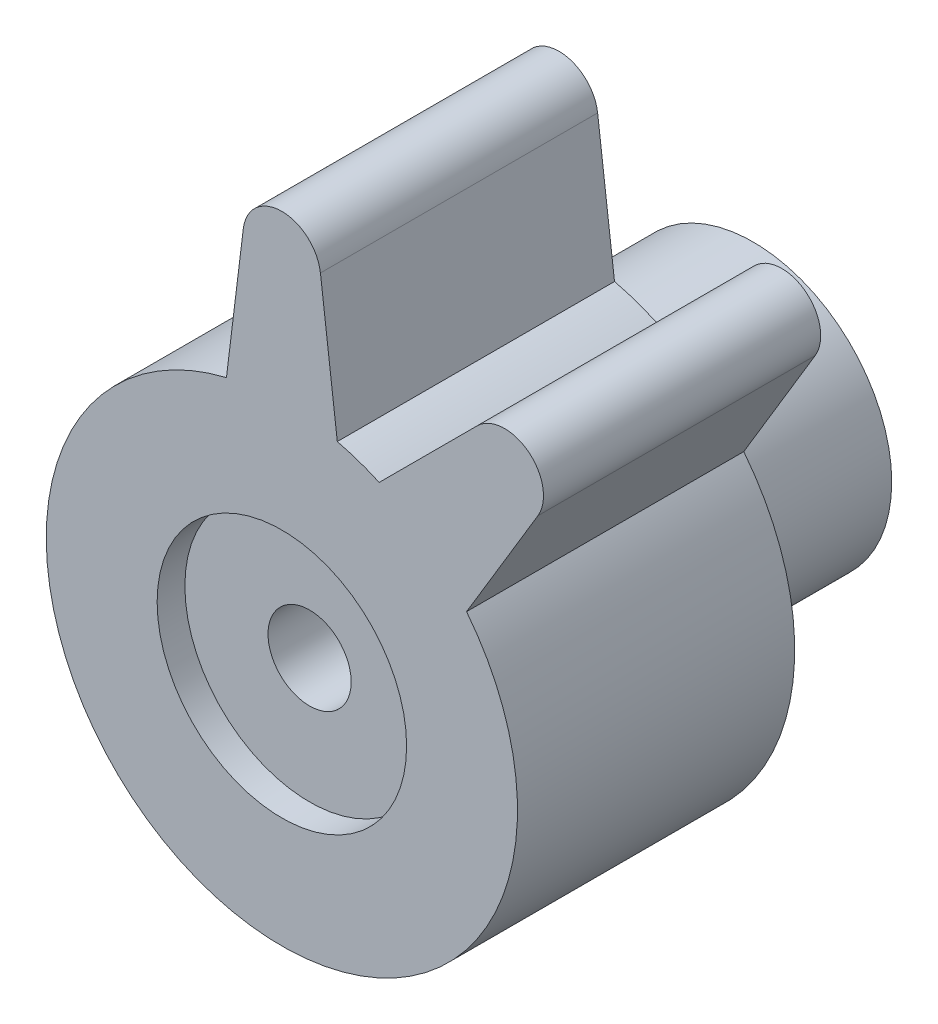
SolidWorks part; units mm, degrees
ref_plane "Front Plane" through (0, 0, 0) normal (0, 0, 1) x (1, 0, 0)
ref_plane "Top Plane" through (0, 0, 0) normal (0, 1, 0) x (1, 0, 0)
ref_plane "Right Plane" through (0, 0, 0) normal (1, 0, 0) x (0, 0, -1)
sketch "Sketch1" plane through (0, 0, 0) normal (0, 0, 1) x (1, 0, 0)
  line L0 (0, 0) -> (0, 51.188) construction
  line L1 (-2, 8.2614) -> (-1.3907, 13.2241)
  line L2 (2, 8.2614) -> (1.3907, 13.2241)
  line L3 (0, 0) -> (22.4184, 65.1077) construction
  line L4 (6.6622, 5.2787) -> (9.2374, 9.5646)
  line L5 (0, 0) -> (31.5145, 40.3367) construction
  line L6 (3.5102, 7.7414) -> (7.0457, 11.2769)
  circle A0 centre (0, 0) radius 8.5
  circle A1 centre (0, 0) radius 1.5
  arc A2 (-1.3907, 13.2241) -> (1.3907, 13.2241) centre (0, 13.0533) cw
  arc A3 (9.2374, 9.5646) -> (7.0457, 11.2769) centre (8.0364, 10.2862) ccw
  circle A4 centre (0, 0) radius 12 construction
  dimension "D1" = 24
  dimension "D2" = 17
  dimension "D3" = 3
  dimension "D4" = 7
  dimension "D7" = 5
  dimension "D5" = 4
  dimension "D6" = 19
extrude "Boss-Extrude1" add sketch "Sketch1" along normal blind 10
sketch "Sketch5" plane through (0, 0, 0) normal (0, 0, -1) x (-1, 0, 0)
  line L0 (1.95, -2.6) -> (-1.95, -2.6)
  circle A0 centre (0, 0) radius 3.25
  circle A1 centre (0, 0) radius 5
  dimension "D1" = 10
  dimension "D2" = 6.5
  dimension "D3" = 2.6
extrude "Boss-Extrude3" add sketch "Sketch5" along normal blind 7 contours A1 A0 | L0 A0
sketch "Sketch8" plane through (0, 0, 10) normal (0, 0, 1) x (1, 0, 0)
  circle A0 centre (0, 0) radius 4.5
  dimension "D1" = 9
extrude "Cut-Extrude2" cut sketch "Sketch8" against normal blind 1
sketch "Sketch9" plane through (0, -2.6, 0) normal (0, 1, 0) x (1, 0, 0)
  line L0 (-1.95, 7) -> (1.95, 7) construction
  line L2 (-1.95, 4) -> (1.95, 4) construction
  line L3 (-1.95, 7) -> (-1.95, 0) construction
  line L4 (1.95, 7) -> (1.95, 0) construction
  circle A0 centre (0, 4) radius 1.5
  dimension "D1" = 3
  dimension "D2" = 3
